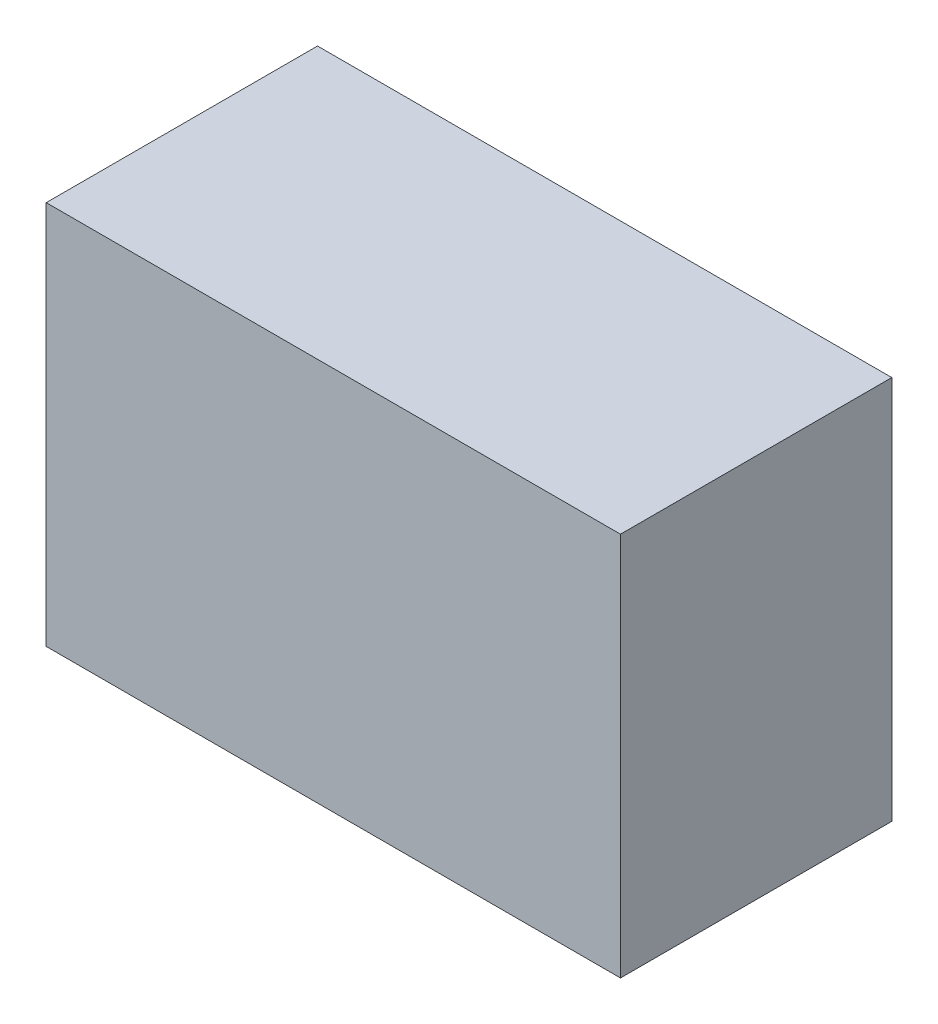
SolidWorks part; units mm, degrees
ref_plane "Front Plane" through (0, 0, 0) normal (0, 0, 1) x (1, 0, 0)
ref_plane "Top Plane" through (0, 0, 0) normal (0, 1, 0) x (1, 0, 0)
ref_plane "Right Plane" through (0, 0, 0) normal (1, 0, 0) x (0, 0, -1)
sketch "Sketch1" plane through (0, 0, 0) normal (0, 0, 1) x (1, 0, 0)
  line L1 (-31.75, -21.25) -> (31.75, -21.25)
  line L2 (-31.75, -21.25) -> (-31.75, 21.25)
  line L3 (-31.75, 21.25) -> (31.75, 21.25)
  line L4 (31.75, -21.25) -> (31.75, 21.25)
  line L5 (-31.75, -21.25) -> (31.75, 21.25) construction
  line L6 (-31.75, 21.25) -> (31.75, -21.25) construction
  point P0 (0, 0)
  dimension "D1" = 63.5
  dimension "D2" = 42.5
extrude "Boss-Extrude1" add sketch "Sketch1" along normal blind 30
